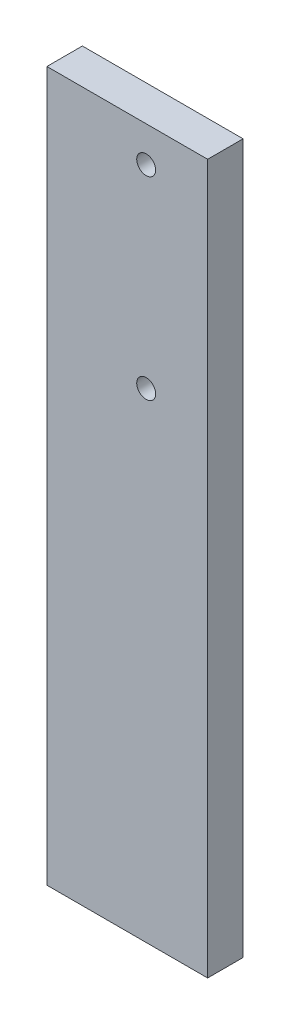
SolidWorks part; units mm, degrees
ref_plane "Alzado" through (0, 0, 0) normal (0, 0, 1) x (1, 0, 0)
ref_plane "Planta" through (0, 0, 0) normal (0, 1, 0) x (1, 0, 0)
ref_plane "Vista lateral" through (0, 0, 0) normal (1, 0, 0) x (0, 0, -1)
sketch "Croquis1" plane through (0, 0, 0) normal (0, 0, 1) x (1, 0, 0)
  line L1 (0, 0) -> (68, 0)
  line L2 (0, 0) -> (0, 300)
  line L3 (0, 300) -> (68, 300)
  line L4 (68, 0) -> (68, 300)
  circle A0 centre (42, 285) radius 4
  circle A1 centre (42, 203) radius 4
  dimension "D3" = 8
  dimension "D1" = 300
  dimension "D2" = 68
  dimension "D4" = 82
  dimension "D5" = 15
  dimension "D6" = 26
extrude "Saliente-Extruir1" add sketch "Croquis1" along normal blind 15
